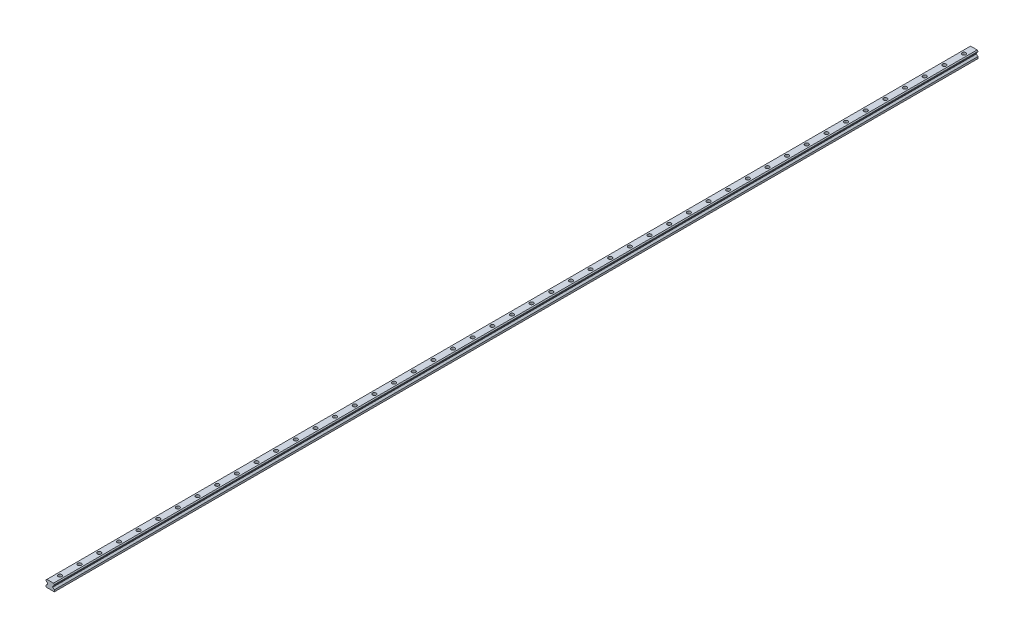
SolidWorks part; units mm, degrees
material "一般碳鋼"
ref_plane "前基準面" through (0, 0, 0) normal (0, 0, 1) x (1, 0, 0)
ref_plane "上基準面" through (0, 0, 0) normal (0, 1, 0) x (1, 0, 0)
ref_plane "右基準面" through (0, 0, 0) normal (1, 0, 0) x (0, 0, -1)
sketch "草圖1" plane through (0, 0, 0) normal (0, 0, 1) x (1, 0, 0)
  line L0 (17, 0) -> (-17, 0)
  line L1 (-17, 0) -> (-17, 7.5)
  line L2 (-17, 7.5) -> (-10, 12.7214)
  line L3 (-10, 12.7214) -> (-10, 16.1299)
  line L4 (-10, 16.1299) -> (-17, 23.1299)
  line L5 (-17, 23.1299) -> (-17, 25.4259)
  line L6 (-17, 25.4259) -> (-13.4259, 29)
  line L7 (-13.4259, 29) -> (13.4259, 29)
  line L8 (0, 29) -> (0, 0) construction
  line L9 (17, 25.4259) -> (13.4259, 29)
  line L10 (17, 23.1299) -> (17, 25.4259)
  line L11 (10, 16.1299) -> (17, 23.1299)
  line L12 (10, 12.7214) -> (10, 16.1299)
  line L13 (17, 7.5) -> (10, 12.7214)
  line L14 (17, 0) -> (17, 7.5)
  dimension "D1" = 17
  dimension "D2" = 7.5
  dimension "D3" = 29
  dimension "D4" = 135
  dimension "D5" = 135
  dimension "D6" = 10
extrude "伸長1" add sketch "草圖1" along normal mid plane 3760
hole_wizard "M8 內六角圓柱頭螺釘的柱孔1" positions "草圖3" profile "草圖2" counterbore size "M8" standard "GB" end condition through all
sketch "草圖3" plane through (0, 29, 0) normal (0, 1, 0) x (-1, 0, 0)
  line L0 (0, 1880) -> (0, 701.4527) construction
  line L1 (-13.4259, 1880) -> (13.4259, 1880) construction
  line L6 (0, -1880) -> (0, -1840) construction
  line L7 (-13.4259, -1880) -> (13.4259, -1880) construction
  point P0 (0, -1840)
  dimension "D1" = 40
sketch "草圖2" plane through (0, 29, -1840) normal (1, 0, 0) x (0, 0, 1)
  line L0 (0, 0) -> (0, 29)
  line L1 (0, 29) -> (4.5, 29)
  line L3 (4.5, 29) -> (4.5, 12)
  line L4 (4.5, 12) -> (7.5, 12)
  line L5 (7.5, 12) -> (7.5, 0)
  line L7 (7.5, 0) -> (0, 0)
  line L11 (0, -6.35) -> (0, 107.95) construction
  dimension "貫穿孔直徑" = 9
  dimension "貫穿孔深度" = 29
  dimension "柱孔直徑" = 15
  dimension "柱孔深度" = 12
pattern_linear "直線複製排列1" count 47 spacing 80 along (0, 0, 1) of "M8 內六角圓柱頭螺釘的柱孔1"
